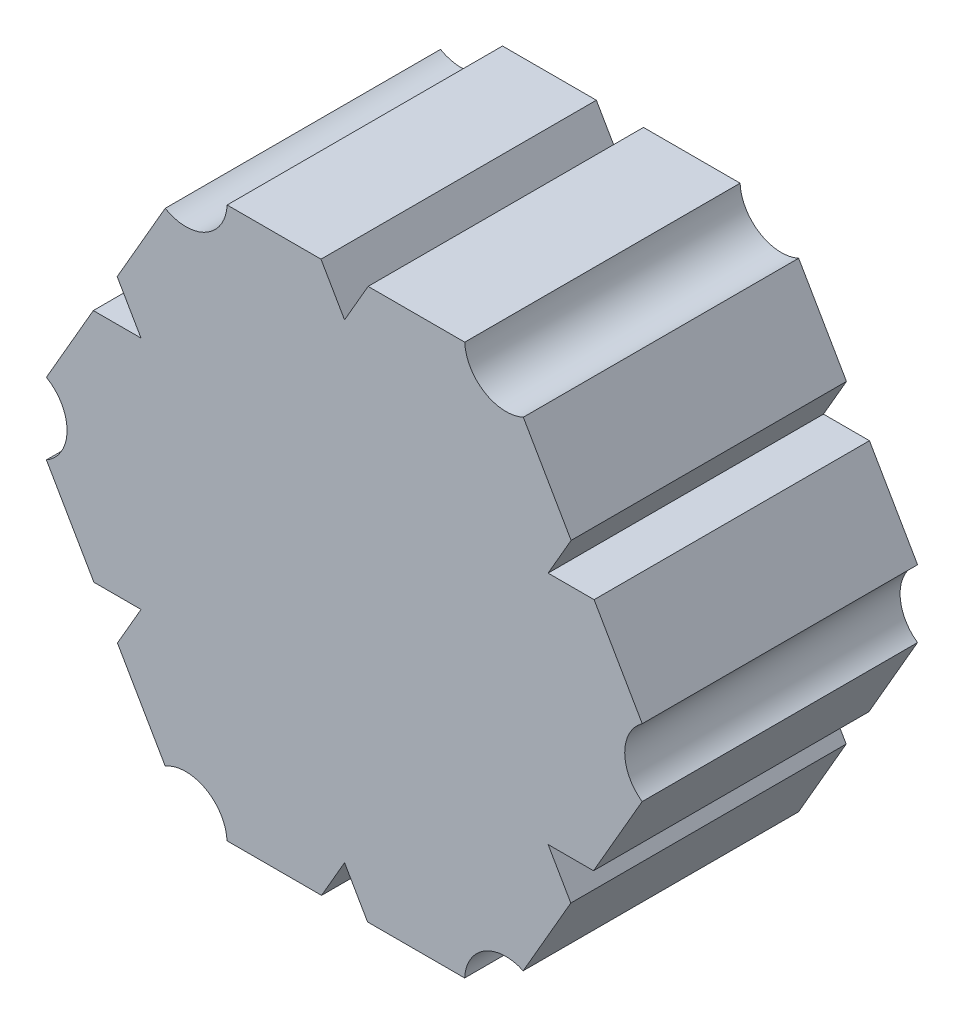
SolidWorks part; units mm, degrees
ref_plane "前视基准面" through (0, 0, 0) normal (0, 0, 1) x (1, 0, 0)
ref_plane "上视基准面" through (0, 0, 0) normal (0, 1, 0) x (1, 0, 0)
ref_plane "右视基准面" through (0, 0, 0) normal (1, 0, 0) x (0, 0, -1)
other "Configuration Table"
sketch "草图1" plane through (0, 0, 0) normal (0, 0, 1) x (1, 0, 0)
  line L1 (23.094, 0) -> (11.547, 20)
  line L2 (11.547, 20) -> (-11.547, 20)
  line L3 (-11.547, 20) -> (-23.094, 0)
  line L4 (-23.094, 0) -> (-11.547, -20)
  line L5 (-11.547, -20) -> (11.547, -20)
  line L6 (11.547, -20) -> (23.094, 0)
  circle A0 centre (0, 0) radius 20 construction
extrude "凸台-拉伸1" add sketch "草图1" along normal mid plane 20
sketch "草图2" plane through (0, 0, 10) normal (0, 0, 1) x (1, 0, 0)
  line L0 (-11.547, 20) -> (-23.094, 0) construction
  line L2 (-14.7224, 8.5) -> (-17.3205, 13)
  line L3 (-17.3205, 13) -> (-19.9186, 8.5)
  line L4 (-19.9186, 8.5) -> (-14.7224, 8.5)
  circle A0 centre (-17.3205, 10) radius 1.5 construction
extrude "切除-拉伸1" cut sketch "草图2" against normal blind 20
pattern_circular "阵列(圆周)1" count 6 over 360 about axis through (0.0619, -0.0358, 0) along (0, 0, 1) of "切除-拉伸1"
sketch "草图3" plane through (0, 0, 10) normal (0, 0, 1) x (1, 0, 0)
  circle A0 centre (-23.094, 0) radius 3
extrude "切除-拉伸2" cut sketch "草图3" against normal blind 20
pattern_circular "阵列(圆周)2" count 6 over 360 about axis through (0.158, -0.0046, 0) along (0, 0, 1) of "切除-拉伸2"
